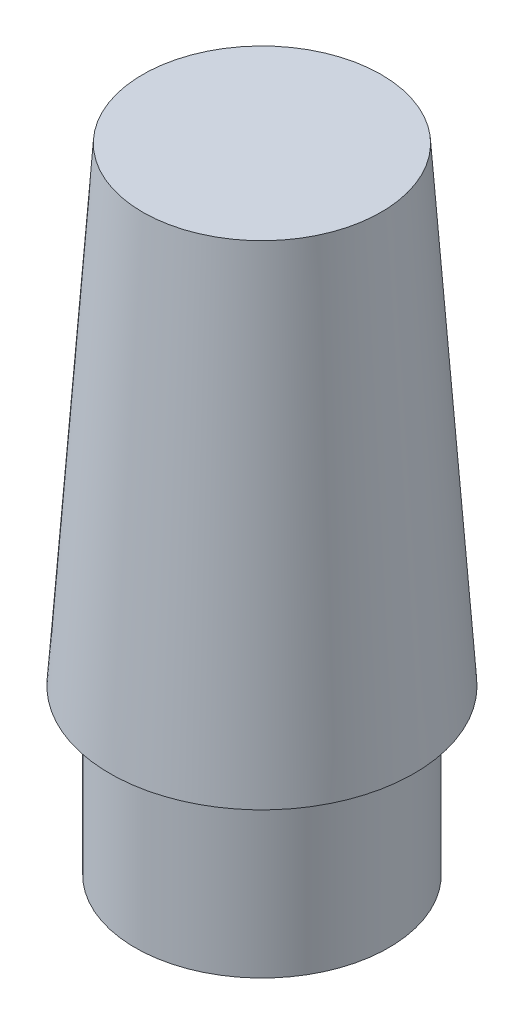
SolidWorks part; units mm, degrees
ref_plane "Front Plane" through (0, 0, 0) normal (0, 0, 1) x (1, 0, 0)
ref_plane "Top Plane" through (0, 0, 0) normal (0, 1, 0) x (1, 0, 0)
ref_plane "Right Plane" through (0, 0, 0) normal (1, 0, 0) x (0, 0, -1)
sketch "Sketch1" plane through (0, 0, 0) normal (0, 1, 0) x (1, 0, 0)
  circle A0 centre (0, 0) radius 15.35
  dimension "D1" = 30.7
extrude "Boss-Extrude1" add sketch "Sketch1" along normal blind 63.9
sketch "Sketch2" plane through (0, 0, 0) normal (0, -1, 0) x (1, 0, 0)
  line L0 (-10.8, -6.8702) -> (-10.8, 6.8702)
  arc A0 (-10.8, 6.8702) -> (-10.8, -6.8702) centre (0, 0) cw
  point P3 (-10.8, 0)
  point P6 (12.8, 0)
  circle M4 centre (0, 0) radius 15.35
  dimension "D2" = 25.6
  dimension "D1" = 23.6
extrude "Cut-Extrude1" cut sketch "Sketch2" against normal blind 16.5 contours L0 A0 M4
draft "Draft3" type of draft neutral plane draft angle 4 faces to draft 1 face at (0, 63.9, 15.35) neutral plane through (0, 16.5, 0) neutral plane normal (0, -1, 0) reverse direction yes parameters "D1"=4
